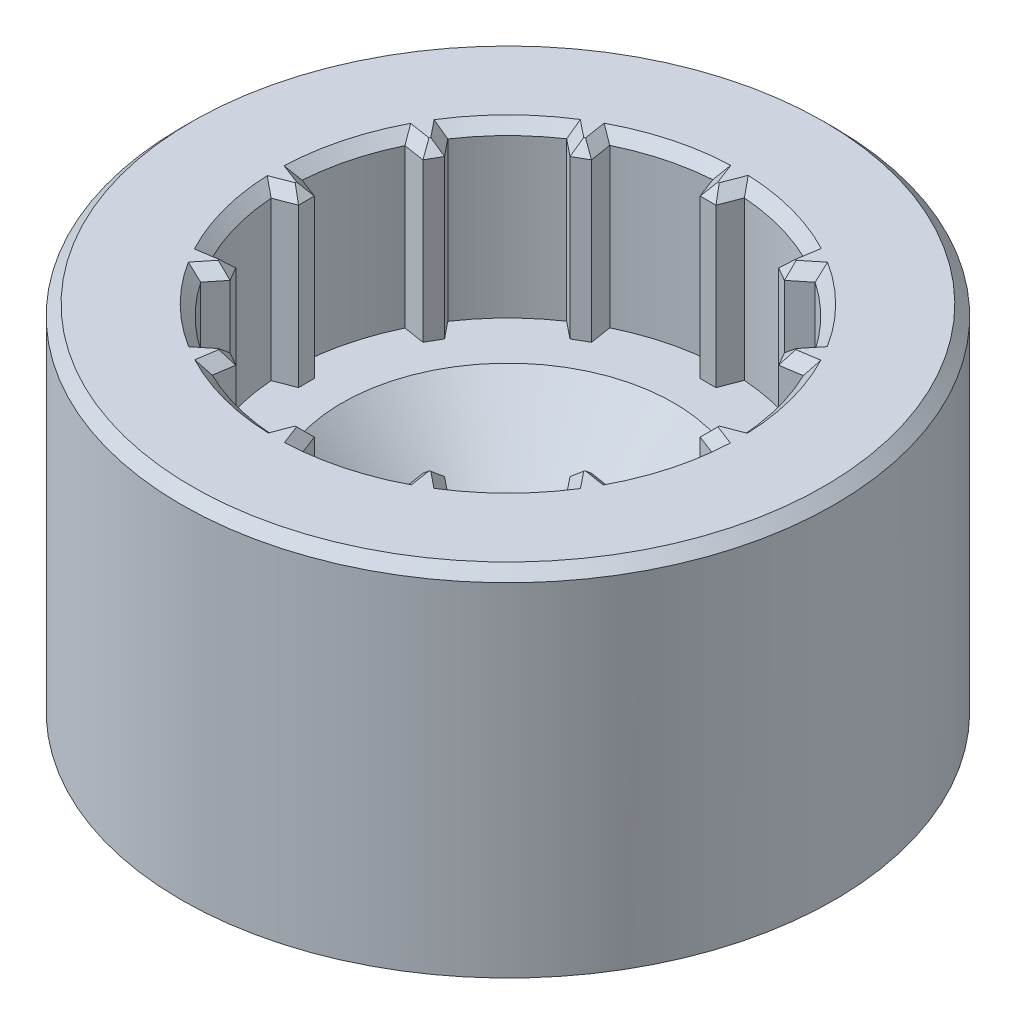
SolidWorks part; units mm, degrees
material "尼龙 101"
ref_plane "前视基准面" through (0, 0, 0) normal (0, 0, 1) x (1, 0, 0)
ref_plane "上视基准面" through (0, 0, 0) normal (0, 1, 0) x (1, 0, 0)
ref_plane "右视基准面" through (0, 0, 0) normal (1, 0, 0) x (0, 0, -1)
sketch "草图1" plane through (0, 0, 0) normal (0, 0, 1) x (1, 0, 0)
  line L0 (0, 0) -> (0, -25370.8813) construction
  line L1 (0, 2) -> (4.2, 2)
  line L2 (4.2, 2) -> (4.2, 5.2)
  line L3 (4.2, 5.2) -> (6.2, 5.2)
  line L4 (6.2, 5.2) -> (6.2, -1.5)
  line L7 (6.2, -1.5) -> (2, -1.5)
  line L8 (2, -1.5) -> (2, 0)
  line L9 (2, 0) -> (0, 0)
  line L10 (0, 0) -> (0, 2)
  dimension "D1" = 2
  dimension "D2" = 4.2
  dimension "D3" = 2
  dimension "D4" = 1.5
  dimension "D5" = 2
  dimension "D6" = 3.2
revolve "旋转1" add sketch "草图1" angle 360 about L0
sketch "草图6" plane through (0, 5.2, 0) normal (0, 1, 0) x (1, 0, 0)
  line L0 (-0.3, 4.1893) -> (-0.15, 3.8)
  line L1 (-0.15, 3.8) -> (0.15, 3.8)
  line L2 (0.15, 3.8) -> (0.3, 4.1893)
  line L3 (0, 3.8) -> (0, 0) construction
  circle A0 centre (0, 0) radius 4.2 construction
  arc A1 (0.3, 4.1893) -> (-0.3, 4.1893) centre (0, 0) ccw
  point P2 (0, 4.2)
  dimension "D1" = 0.4
  dimension "D2" = 0.3
  dimension "D3" = 0.6
extrude "凸台-拉伸1" add sketch "草图6" against normal up to next
pattern_circular "阵列(圆周)1" count 12 over 360 about axis through (0, 0, 0.0131) along (0, 1, 0) of "凸台-拉伸1"
chamfer "倒角1" distance 0.2 angle 45 49 edges at (-0.2201, 5.2, 4.008) (0.2201, 5.2, 4.008) (0, 5.2, 3.8261) (2.963, 5.2, 2.9766) (1.807, 5.2, 3.5835) (2.189, 5.2, 3.3635) (1.9065, 5.2, 3.3153) (4.0535, 5.2, 1.0997) (3.3516, 5.2, 2.2035) (3.5736, 5.2, 1.8205) (3.3022, 5.2, 1.9196) (4.0603, 5.2, -1.0744) (4.0009, 5.2, 0.2354) (4.0018, 5.2, -0.2097) (3.8131, 5.2, 0.0131) (2.9766, 5.2, -2.963) (3.5795, 5.2, -1.7953) (3.3564, 5.2, -2.1833) (3.3022, 5.2, -1.8935) (1.0904, 5.2, -4.056) (2.1978, 5.2, -3.3445) (1.8089, 5.2, -3.5695) (1.9065, 5.2, -3.2891) (-1.0904, 5.2, -4.056) (-0.225, 5.2, -3.9946) (0, 5.2, -3.8) (0.225, 5.2, -3.9946) (-2.9766, 5.2, -2.963) (-1.8089, 5.2, -3.5695) (-2.1978, 5.2, -3.3445) (-1.9065, 5.2, -3.2891) (-4.0603, 5.2, -1.0744) (-3.3564, 5.2, -2.1833) (-3.5795, 5.2, -1.7953) (-3.3022, 5.2, -1.8935) (-4.0535, 5.2, 1.0997) (-4.0018, 5.2, -0.2097) (-4.0009, 5.2, 0.2354) (-3.8131, 5.2, 0.0131) (-2.963, 5.2, 2.9766) (-3.5736, 5.2, 1.8205) (-3.3516, 5.2, 2.2035) (-3.3022, 5.2, 1.9196) (0, 5.2, 6.2) (-1.0836, 5.2, 4.0578) (-2.189, 5.2, 3.3635) (-1.807, 5.2, 3.5835) (-1.9065, 5.2, 3.3153) (1.0836, 5.2, 4.0578)
hole_wizard "M3 平头机械螺钉的锥形沉头孔1" positions "草图2" profile "草图3" countersink size "M3" standard "ANSI Metric"
sketch "草图2" plane through (0, 2, 0) normal (0, 1, 0) x (1, 0, 0)
  point P0 (0, 0)
sketch "草图3" plane through (0, 2, 0) normal (1, 0, 0) x (0, 0, 1)
  line L0 (0, 0) -> (0, 10.9614)
  line L1 (0, 10.9614) -> (1.6, 10)
  line L2 (1.6, 10) -> (1.6, 1.55)
  line L3 (1.6, 1.55) -> (3.15, 0)
  line L5 (3.15, 0) -> (0, 0)
  line L6 (-1.6, 1.55) -> (-3.15, 0) construction
  line L10 (0, 10.9614) -> (-1.6, 10) construction
  line L11 (0, -6.35) -> (0, 107.95) construction
  dimension "孔直径" = 3.2
  dimension "孔深度" = 10
  dimension "近端锥形沉头孔直径" = 6.3
  dimension "近端锥形沉头孔角度" = 90
  dimension "导头角度" = 118
